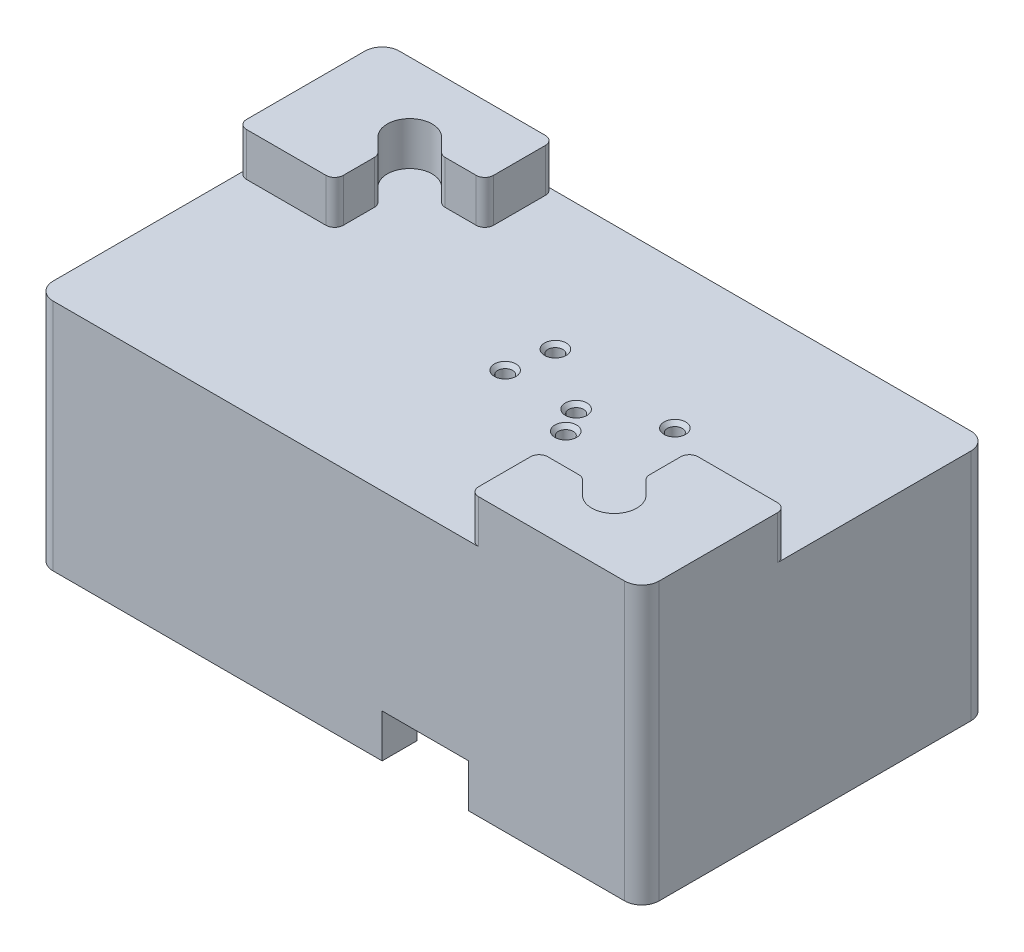
SolidWorks part; units mm, degrees
ref_plane "Front" through (0, 0, 0) normal (0, 0, 1) x (1, 0, 0)
ref_plane "Top" through (0, 0, 0) normal (0, 1, 0) x (1, 0, 0)
ref_plane "Right" through (0, 0, 0) normal (1, 0, 0) x (0, 0, -1)
sketch "Sketch1" plane through (0, 0, 0) normal (0, 1, 0) x (1, 0, 0)
  line L0 (-22.225, -12.7) -> (22.225, 12.7) construction
  line L1 (-22.225, 12.7) -> (22.225, 12.7)
  line L2 (-22.225, 12.7) -> (-22.225, -12.7)
  line L3 (-22.225, -12.7) -> (22.225, -12.7)
  line L4 (22.225, 12.7) -> (22.225, -12.7)
  point P4 (0, 0)
  dimension "D1" = 44.45
  dimension "D2" = 25.4
extrude "Boss-Extrude1" add sketch "Sketch1" along normal blind 17.145
sketch "Sketch2" plane through (0, 17.145, 0) normal (0, 1, 0) x (1, 0, 0)
  line L0 (22.225, 12.7) -> (-22.225, 12.7) construction
  line L1 (-22.225, 12.7) -> (-9.6151, 12.7)
  line L2 (-22.225, 12.7) -> (-22.225, -12.7) construction
  line L3 (-9.6151, 12.7) -> (-9.6151, 7.625)
  line L4 (-9.6151, 7.625) -> (-12.7901, 7.625)
  line L5 (-15.125, 5.2901) -> (-15.125, 2.1151)
  line L6 (-15.125, 2.1151) -> (-22.225, 2.1151)
  line L8 (-22.225, 2.1151) -> (-22.225, 12.7)
  line L9 (22.225, -12.7) -> (22.225, -2.1151)
  line L10 (22.225, -12.7) -> (22.225, 12.7) construction
  line L11 (22.225, -2.1151) -> (15.125, -2.1151)
  line L12 (15.125, -2.1151) -> (15.125, -5.2901)
  line L15 (9.6151, -7.625) -> (9.6151, -12.7)
  line L16 (-22.225, -12.7) -> (22.225, -12.7) construction
  line L17 (9.6151, -12.7) -> (22.225, -12.7)
  line L18 (-13.9576, 8.7924) -> (-12.7901, 7.625)
  line L21 (-16.2924, 6.4576) -> (-15.125, 5.2901)
  line L22 (13.9576, -8.7924) -> (12.7901, -7.625)
  line L23 (16.2924, -6.4576) -> (15.125, -5.2901)
  line L24 (12.7901, -7.625) -> (9.6151, -7.625)
  arc A0 (-13.9576, 8.7924) -> (-16.2924, 6.4576) centre (-15.125, 7.625) ccw
  arc A1 (13.9576, -8.7924) -> (16.2924, -6.4576) centre (15.125, -7.625) ccw
  dimension "D5" = 3.175
  dimension "D1" = 45
  dimension "D2" = 1.651
  dimension "D3" = 30.25
  dimension "D4" = 15.25
  dimension "D6" = 3.175
extrude "Boss-Extrude2" add sketch "Sketch2" along normal blind 3.175
sketch "Sketch3" plane through (0, 17.145, 0) normal (0, 1, 0) x (1, 0, 0)
  line L0 (-12.7901, 7.625) -> (-9.6151, 7.625) construction
  line L1 (-15, 7.5) -> (15, 7.5) construction
  line L2 (-15, 7.5) -> (-15, -7.5) construction
  line L3 (-15, -7.5) -> (15, -7.5) construction
  line L4 (15, 7.5) -> (15, -7.5) construction
  point P4 (0, 7.5)
  point P8 (9.92, 2.025)
  point P9 (6.11, -2.166)
  point P10 (0.522, 2.66)
  point P11 (5.094, -0.388)
  point P12 (0.014, -0.515)
  dimension "D1" = 30
  dimension "D2" = 15
  dimension "D3" = 0.125
  dimension "D4" = 9.525
  dimension "D5" = 5.08
  dimension "D6" = 5.334
  dimension "D7" = 8.89
  dimension "D8" = 9.906
  dimension "D9" = 7.112
  dimension "D10" = 14.478
  dimension "D11" = 10.16
  dimension "D12" = 14.986
  dimension "D13" = 6.985
sketch "Sketch6" plane through (0, 0, 0) normal (0, -1, 0) x (1, 0, 0)
  line L4 (3.175, 10.16) -> (3.175, 12.7)
  line L5 (-22.225, 12.7) -> (22.225, 12.7) construction
  line L6 (3.175, 12.7) -> (9.525, 12.7)
  line L7 (9.525, 12.7) -> (9.525, 10.16)
  line L8 (-19.685, 10.16) -> (-19.685, -10.16)
  line L9 (-19.685, -10.16) -> (19.685, -10.16)
  line L10 (19.685, -10.16) -> (19.685, 10.16)
  line L11 (19.685, 10.16) -> (-19.685, 10.16)
  line L12 (-19.685, 10.16) -> (-19.685, -10.16)
  line L13 (-19.685, -10.16) -> (19.685, -10.16)
  line L14 (19.685, -10.16) -> (19.685, 10.16)
  line L15 (19.685, 10.16) -> (9.525, 10.16)
  line L16 (3.175, 10.16) -> (-19.685, 10.16)
  line L17 (22.225, 12.7) -> (22.225, -12.7) construction
  dimension "D1" = 2.54
  dimension "D2" = 6.35
  dimension "D3" = 12.7
extrude "Cut-Extrude1" cut sketch "Sketch6" against normal blind 3.175
hole_wizard "#57 (0.043) Diameter Hole1" positions "Sketch5" profile "Sketch4" hole size "#57" standard "ANSI Inch" end condition through all
sketch "Sketch5" plane through (0, 17.145, 0) normal (0, 1, 0) x (1, 0, 0)
  point P0 (9.92, 2.025)
  point P3 (6.11, -2.166)
  point P6 (5.094, -0.388)
  point P9 (0.014, -0.515)
  point P12 (0.522, 2.66)
sketch "Sketch4" plane through (9.92, 17.145, -2.025) normal (1, 0, 0) x (0, 0, 1)
  line L0 (0, 0) -> (0, 13.97)
  line L1 (0, 13.97) -> (0.7937, 13.97)
  line L2 (0.5461, 13.6851) -> (0.5461, 0.2849)
  line L3 (0.5461, 0.2849) -> (0.7937, 0)
  line L5 (0.7937, 0) -> (0, 0)
  line L6 (-0.5461, 0.2849) -> (-0.7937, 0) construction
  line L7 (0.7937, 13.97) -> (0.5461, 13.6851)
  line L8 (-0.7938, 13.97) -> (-0.5461, 13.6851) construction
  line L11 (0, -6.35) -> (0, 107.95) construction
  dimension "Thru Hole Dia." = 1.0922
  dimension "Thru Hole Depth" = 13.97
  dimension "Near C'Sink Dia." = 1.5875
  dimension "Near C'Sink Angle" = 82
  dimension "Far C'Sink Dia." = 1.5875
  dimension "Far C'Sink Angle" = 82
fillet "Fillet1" radius 0.635 12 edges at (9.6151, 18.7325, 12.7) (22.225, 18.7325, 2.1151) (9.6151, 18.7325, 7.625) (12.7901, 18.7325, 7.625) (15.125, 18.7325, 5.2901) (15.125, 18.7325, 2.1151) (-9.6151, 18.7325, -7.625) (-12.7901, 18.7325, -7.625) (-15.125, 18.7325, -5.2901) (-15.125, 18.7325, -2.1151)
fillet "Fillet2" radius 1.27 4 edges at (22.225, 8.5725, -12.7) (22.225, 10.16, 12.7) (-22.225, 8.5725, 12.7) (-22.225, 10.16, -12.7)
chamfer "Chamfer1" [suppressed] distance 0.635 angle 45
fillet "Fillet3" radius 4.826 4 edges at (-19.685, 1.5875, -10.16) (19.685, 1.5875, -10.16) (19.685, 1.5875, 10.16) (-19.685, 1.5875, 10.16)
